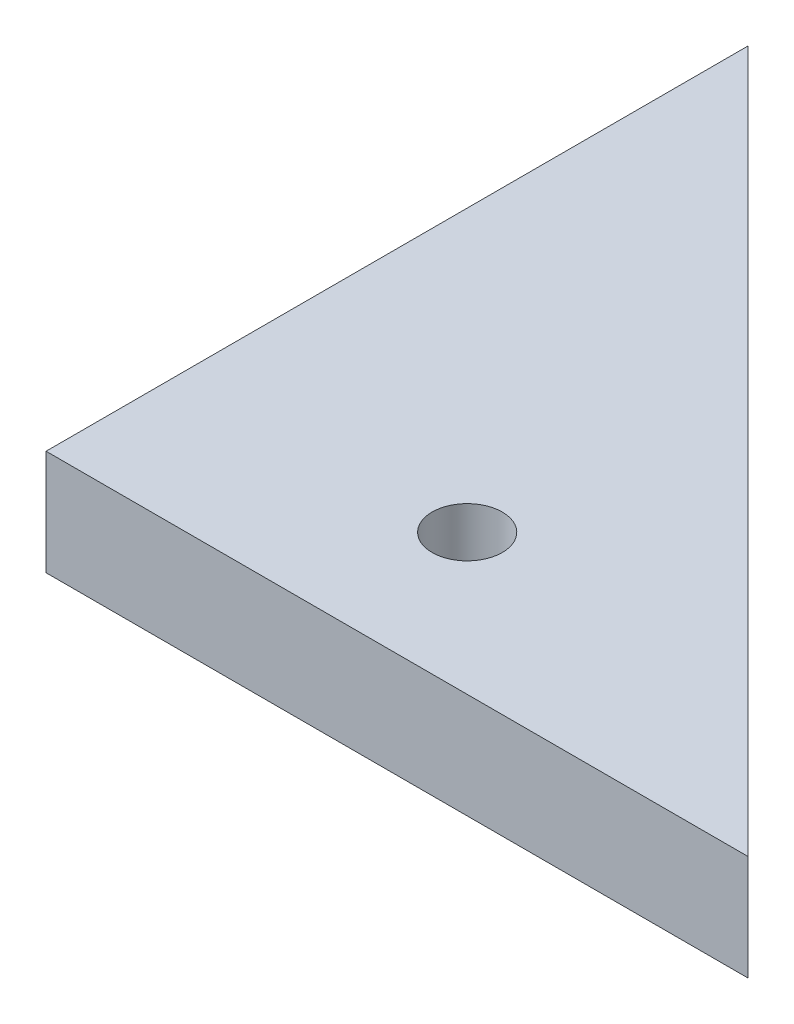
SolidWorks part; units mm, degrees
material "Pine"
ref_plane "Front Plane" through (0, 0, 0) normal (0, 0, 1) x (1, 0, 0)
ref_plane "Top Plane" through (0, 0, 0) normal (0, 1, 0) x (1, 0, 0)
ref_plane "Right Plane" through (0, 0, 0) normal (1, 0, 0) x (0, 0, -1)
sketch "Sketch1" plane through (0, 0, 0) normal (0, 1, 0) x (1, 0, 0)
  line L0 (-14.3583, 0) -> (-14.3583, 127)
  line L1 (-14.3583, 0) -> (112.6417, 0)
  line L2 (-14.3583, 127) -> (112.6417, 0)
  circle A0 centre (36.4417, 25.4) radius 6.35
extrude "Boss-Extrude1" add sketch "Sketch1" along normal blind 19.05
